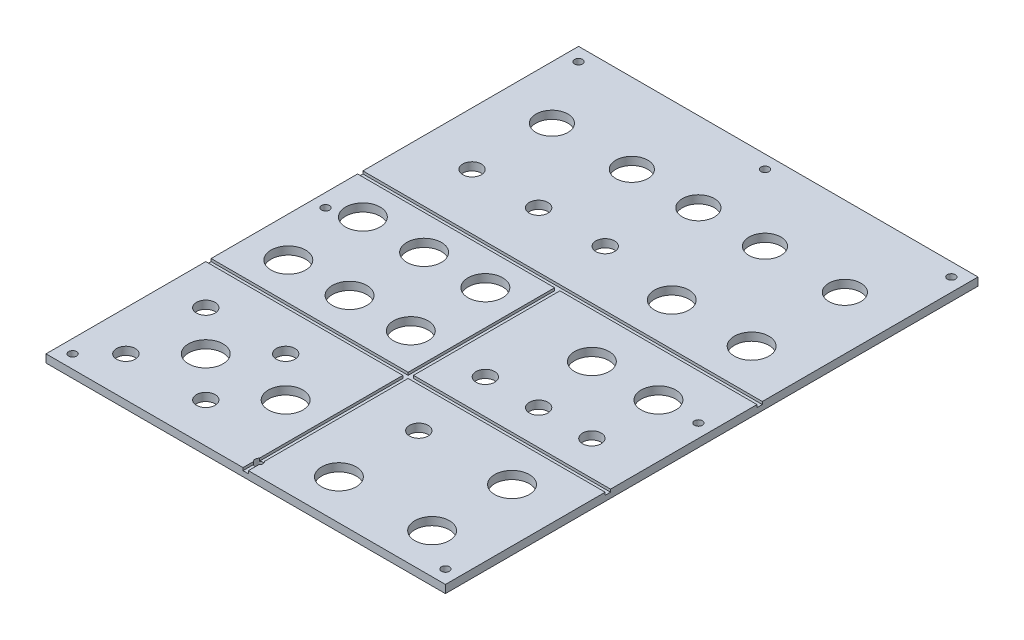
SolidWorks part; units mm, degrees
ref_plane "Front Plane" through (0, 0, 0) normal (0, 0, 1) x (1, 0, 0)
ref_plane "Top Plane" through (0, 0, 0) normal (0, 1, 0) x (1, 0, 0)
ref_plane "Right Plane" through (0, 0, 0) normal (1, 0, 0) x (0, 0, -1)
sketch "Sketch1" plane through (0, 0, 0) normal (0, 1, 0) x (1, 0, 0)
  line L1 (75, -100) -> (-75, -100)
  line L2 (75, -100) -> (75, 100)
  line L3 (75, 100) -> (-75, 100)
  line L4 (-75, -100) -> (-75, 100)
  line L5 (75, -100) -> (-75, 100) construction
  line L6 (75, 100) -> (-75, -100) construction
  point P0 (0, 0)
  dimension "D1" = 150
  dimension "D2" = 200
extrude "Boss-Extrude1" add sketch "Sketch1" along normal blind 3
sketch "Buttons" plane through (0, 3, 0) normal (0, 1, 0) x (1, 0, 0)
  line L0 (75, 100) -> (-75, 100) construction
  line L1 (-75, 100) -> (-75, -100) construction
  line L2 (75, -100) -> (75, 100) construction
  line L3 (20, -85) -> (20, -36.29) construction
  line L4 (-75, -100) -> (75, -100) construction
  line L5 (-60, -55) -> (-60, -85) construction
  line L6 (-60, -70) -> (-30, -70) construction
  line L7 (-30, -55) -> (-30, -85) construction
  line L8 (55, -55) -> (20, -55) construction
  circle A0 centre (-55, 70) radius 6
  circle A1 centre (-25, 70) radius 6
  circle A2 centre (0, 70) radius 6
  circle A3 centre (55, 70) radius 6
  circle A4 centre (55, 35) radius 6.5
  circle A5 centre (25, 35) radius 6.5
  circle A6 centre (55, -55) radius 6.5
  circle A7 centre (-55, 40) radius 3.5
  circle A8 centre (-5, 40) radius 3.5
  circle A9 centre (-30, 40) radius 3.5
  circle A10 centre (55, -85) radius 6.5
  circle A11 centre (20, -85) radius 6.5
  circle A12 centre (20, -55) radius 3.5
  circle A13 centre (-60, -55) radius 3.5
  circle A14 centre (-30, -55) radius 3.5
  circle A15 centre (-60, -85) radius 3.5
  circle A16 centre (-30, -85) radius 3.5
  circle A17 centre (-45, -70) radius 6.5
  circle A18 centre (30, 0) radius 6.5
  circle A19 centre (55, 0) radius 6.5
  circle A20 centre (35, -25) radius 3.5
  circle A21 centre (55, -25) radius 3.5
  circle A22 centre (15, -25) radius 3.5
  circle A23 centre (-60, 4) radius 6.5
  circle A24 centre (-37, 4) radius 6.5
  circle A25 centre (-14, 4) radius 6.5
  circle A26 centre (-60, -24) radius 6.5
  circle A27 centre (-37, -24) radius 6.5
  circle A28 centre (-14, -24) radius 6.5
  circle A29 centre (25, 70) radius 6
  circle A30 centre (-15, -70) radius 6.5
  dimension "D1" = 12
  dimension "D4" = 12
  dimension "D5" = 30
  dimension "D9" = 13
  dimension "D11" = 13
  dimension "D12" = 30
  dimension "D13" = 7
  dimension "D17" = 30
  dimension "D18" = 35
  dimension "D19" = 7
  dimension "D20" = 7
  dimension "D21" = 13
  dimension "D27" = 30
  dimension "D29" = 7
  dimension "D30" = 13
  dimension "D34" = 13
  dimension "D8" = 20
  dimension "D41" = 30
  dimension "D2" = 30
  dimension "D3" = 20
  dimension "D6" = 30
  dimension "D7" = 25
  dimension "D10" = 30
  dimension "D14" = 25
  dimension "D15" = 25
  dimension "D16" = 20
  dimension "D22" = 15
  dimension "D23" = 15
  dimension "D24" = 30
  dimension "D25" = 30
  dimension "D26" = 15
  dimension "D28" = 25
  dimension "D31" = 25
  dimension "D32" = 20
  dimension "D33" = 20
  dimension "D35" = 28
  dimension "D36" = 23
  dimension "D37" = 23
  dimension "D38" = 15
  dimension "D39" = 31
  dimension "D40" = 25
extrude "Cut-Extrude2" cut sketch "Buttons" against normal through all
sketch "Sketch3" plane through (0, 3, 0) normal (0, 1, 0) x (1, 0, 0)
  line L0 (75, -40) -> (1, -40)
  line L1 (75, -100) -> (75, 100) construction
  line L2 (-75, 100) -> (-75, -100) construction
  line L3 (-75, -40) -> (-75, -38)
  line L4 (-75, -38) -> (-1, -38)
  line L5 (75, -38) -> (75, -40)
  line L6 (-1, -100) -> (-1, -40)
  line L7 (-75, -100) -> (75, -100) construction
  line L8 (0, 0) -> (0, -100) construction
  line L9 (1, -40) -> (1, -100)
  line L10 (1, -100) -> (-1, -100)
  line L11 (1, -38) -> (1, 17)
  line L12 (-1, -40) -> (-75, -40)
  line L13 (1, 17) -> (75, 17)
  line L14 (75, 17) -> (75, 19)
  line L15 (75, 19) -> (-75, 19)
  line L16 (-75, 19) -> (-75, 17)
  line L17 (1, -38) -> (75, -38)
  line L18 (-75, 17) -> (-1, 17)
  line L19 (-1, 17) -> (-1, -38)
  dimension "D1" = 2
  dimension "D2" = 2
  dimension "D3" = 60
  dimension "D4" = 2
  dimension "D5" = 55
extrude "Cut-Extrude3" cut sketch "Sketch3" against normal blind 1
sketch "BoxHoles" plane through (0, 3, 0) normal (0, 1, 0) x (1, 0, 0)
  line L0 (-75, 95) -> (75, 95) construction
  line L4 (-75, 100) -> (-75, 19) construction
  line L5 (75, 19) -> (75, 100) construction
  line L6 (75, 100) -> (-75, 100) construction
  line L7 (-70, 100) -> (-70, -100) construction
  line L8 (-75, -100) -> (-1, -100) construction
  line L10 (-75, -95) -> (75, -95) construction
  line L11 (-75, -40) -> (-75, -100) construction
  line L12 (75, -100) -> (75, -40) construction
  line L13 (70, -100) -> (70, 100) construction
  line L14 (1, -100) -> (75, -100) construction
  circle A0 centre (-70, 95) radius 1.5
  circle A1 centre (70, 95) radius 1.5
  circle A2 centre (70, 0) radius 1.5
  circle A3 centre (-70, 0) radius 1.5
  circle A4 centre (-70, -95) radius 1.5
  circle A5 centre (70, -95) radius 1.5
  circle A6 centre (0, 95) radius 1.5
  circle A7 centre (0, -95) radius 1.5
  dimension "D1" = 3
  dimension "D3" = 5
  dimension "D4" = 5
  dimension "D5" = 5
  dimension "D6" = 5
  dimension "D7" = 5
extrude "Box Holes Cut" cut sketch "BoxHoles" against normal through all
equation "\"btn_pit_limit_dia\"= 12mm"
equation "\"D4@Buttons\" = \"btn_pit_limit_dia\""
equation "\"btn_push_switch2_dia\"= 13mm"
equation "\"D9@Buttons\"=\"btn_push_switch2_dia\""
equation "\"btn_rot1_dia\"=7"
equation "\"D13@Buttons\"=\"btn_rot1_dia\""
equation "\"D11@Buttons\"=\"btn_push_switch2_dia\""
equation "\"D19@Buttons\"=\"btn_rot1_dia\""
equation "\"D20@Buttons\"=\"btn_rot1_dia\""
equation "\"D21@Buttons\"=\"btn_push_switch2_dia\""
equation "\"D29@Buttons\"=\"btn_rot1_dia\""
equation "\"D30@Buttons\"=\"btn_push_switch2_dia\""
equation "\"D34@Buttons\"=\"btn_push_switch2_dia\""
equation "\"screw_box_outer\"=3"
equation "\"D1@BoxHoles\"=\"screw_box_outer\""
